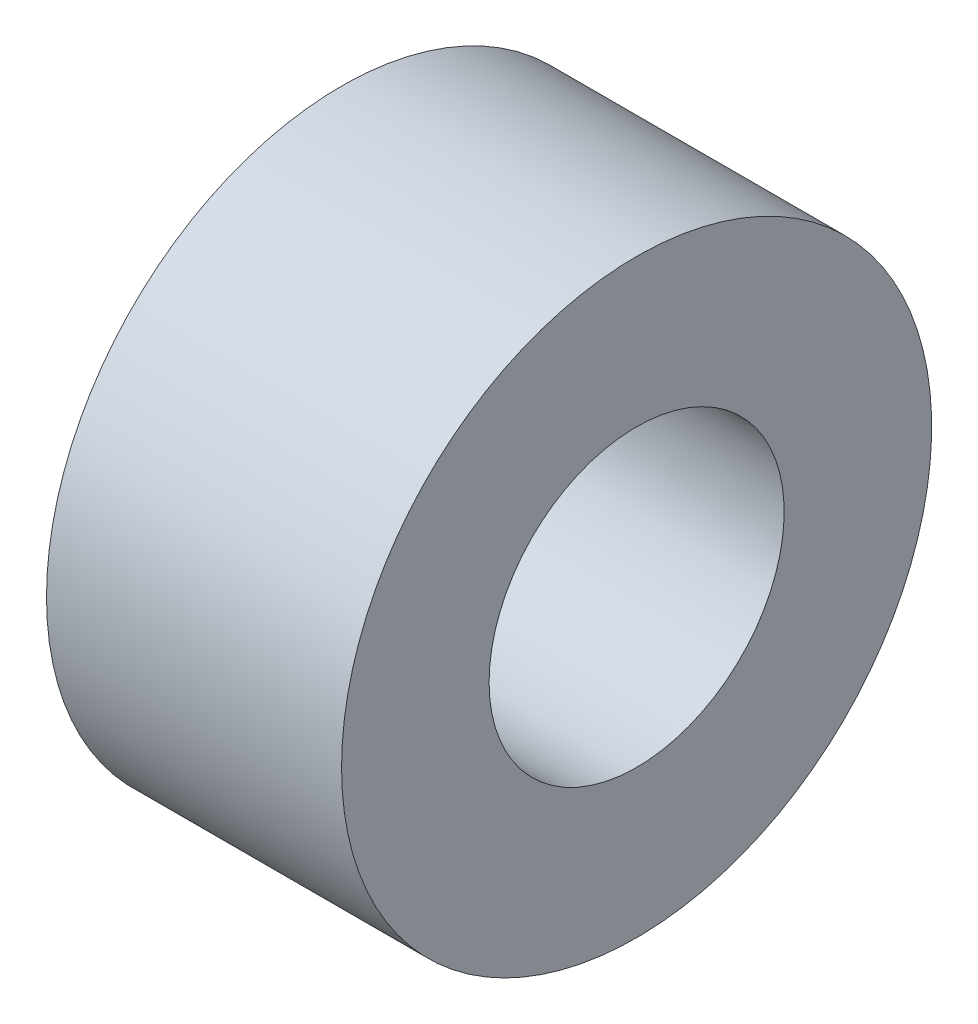
SolidWorks part; units mm, degrees
material "6061 Alloy"
ref_plane "Front Plane" through (0, 0, 0) normal (0, 0, 1) x (1, 0, 0)
ref_plane "Top Plane" through (0, 0, 0) normal (0, 1, 0) x (1, 0, 0)
ref_plane "Right Plane" through (0, 0, 0) normal (1, 0, 0) x (0, 0, -1)
sketch "Sketch1" plane through (0, 0, 0) normal (1, 0, 0) x (0, 0, -1)
  circle A0 centre (0, 0) radius 4.7625
  circle A1 centre (0, 0) radius 9.525
  dimension "D1" = 19.05
  dimension "D2" = 9.525
extrude "Boss-Extrude1" add sketch "Sketch1" along normal blind 9.525
